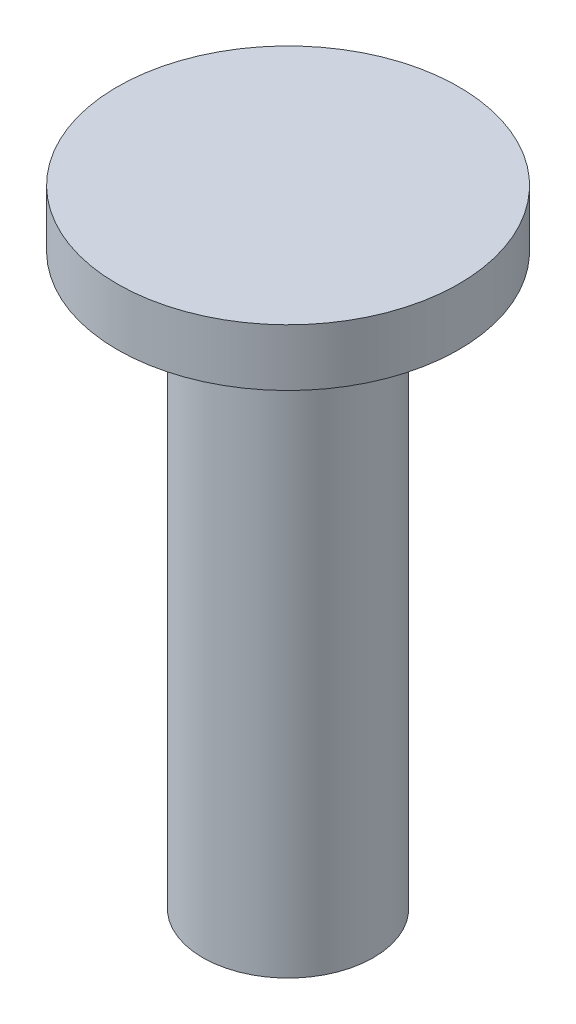
SolidWorks part; units mm, degrees
material "AISI 304"
ref_plane "前视基准面" through (0, 0, 0) normal (0, 0, 1) x (1, 0, 0)
ref_plane "上视基准面" through (0, 0, 0) normal (0, 1, 0) x (1, 0, 0)
ref_plane "右视基准面" through (0, 0, 0) normal (1, 0, 0) x (0, 0, -1)
other "Configuration Table"
sketch "草图1" plane through (0, 0, 0) normal (0, 1, 0) x (1, 0, 0)
  circle A0 centre (0, 0) radius 3
  dimension "D1" = 6
extrude "凸台-拉伸1" add sketch "草图1" along normal blind 1
sketch "草图2" plane through (0, 0, 0) normal (0, -1, 0) x (1, 0, 0)
  circle A0 centre (0, 0) radius 1.5
  dimension "D1" = 3
extrude "凸台-拉伸2" add sketch "草图2" along normal blind 10
